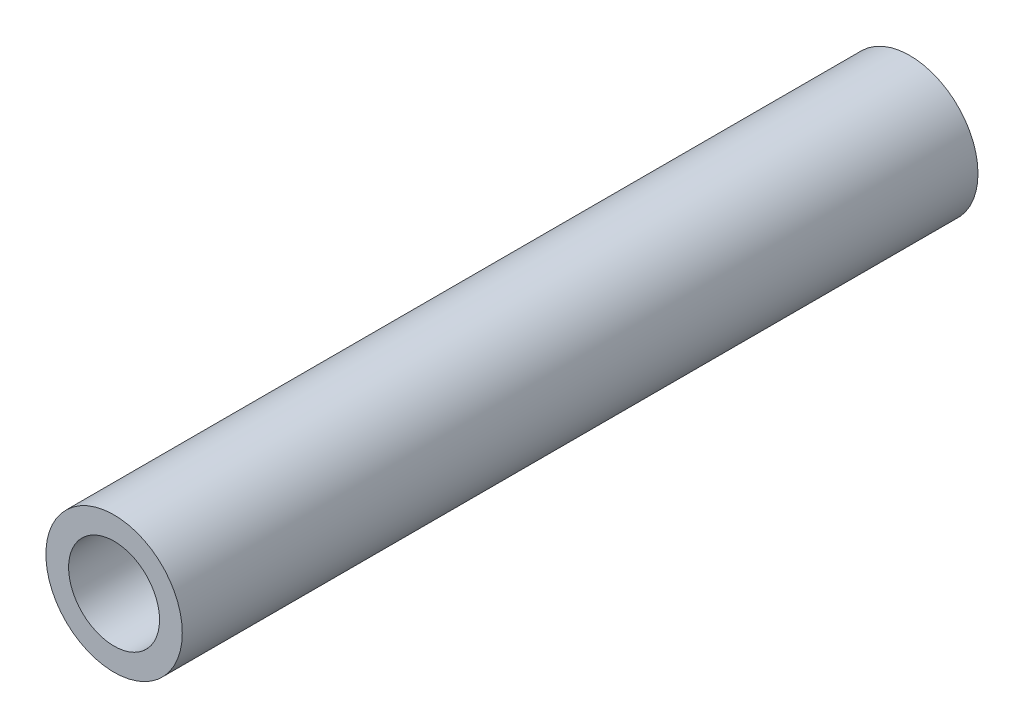
SolidWorks part; units mm, degrees
material "炭素鋼(普通)"
ref_plane "正面" through (0, 0, 0) normal (0, 0, 1) x (1, 0, 0)
ref_plane "平面" through (0, 0, 0) normal (0, 1, 0) x (1, 0, 0)
ref_plane "右側面" through (0, 0, 0) normal (1, 0, 0) x (0, 0, -1)
sketch "ｽｹｯﾁ1" plane through (0, 0, 0) normal (0, 0, 1) x (1, 0, 0)
  circle A0 centre (0, 0) radius 3
  circle A1 centre (0, 0) radius 2
  dimension "D1" = 4
  dimension "D2" = 6
extrude "ﾎﾞｽ - 押し出し1" add sketch "ｽｹｯﾁ1" along normal blind 35
